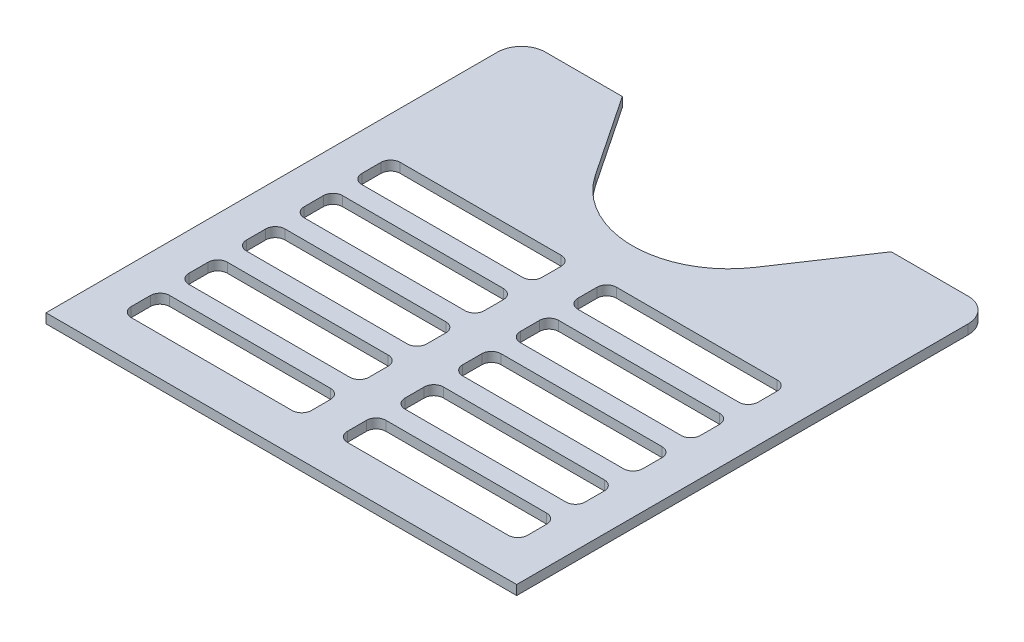
SolidWorks part; units mm, degrees
material "PVC hart"
ref_plane "Ebene vorne" through (0, 0, 0) normal (0, 0, 1) x (1, 0, 0)
ref_plane "Ebene oben" through (0, 0, 0) normal (0, 1, 0) x (1, 0, 0)
ref_plane "Ebene rechts" through (0, 0, 0) normal (1, 0, 0) x (0, 0, -1)
sketch "Skizze2" plane through (0, 0, 0) normal (0, 1, 0) x (1, 0, 0)
  line L0 (0, 82.3632) -> (0, -81.2206) construction
  line L6 (-44, 50) -> (-28, 50)
  line L7 (-28, 50) -> (-16.6199, 33)
  line L8 (28, 50) -> (16.6199, 33)
  line L9 (44, 50) -> (28, 50)
  line L10 (-49, -49) -> (-49, 45)
  line L11 (49, -49) -> (49, 45)
  line L12 (-49, -49) -> (49, -49)
  arc A0 (-16.6199, 33) -> (16.6199, 33) centre (0, 44.1257) ccw
  arc A1 (49, 45) -> (44, 50) centre (44, 45) ccw
  arc A2 (-49, 45) -> (-44, 50) centre (-44, 45) cw
  point P0 (0, 0)
  point P3 (49, 50)
  point P16 (-49, 50)
  dimension "D1" = 20
  dimension "D8" = 5
  dimension "D2" = 49
  dimension "D3" = 99
  dimension "D4" = 21
  dimension "D5" = 17
  dimension "D6" = 49
  dimension "D7" = 49
extrude "Aufsatz-Linear austragen2" add sketch "Skizze2" along normal blind 2
sketch "Skizze3" plane through (0, 2, 0) normal (0, 1, 0) x (1, 0, 0)
  line L0 (0, 51.615) -> (0, -55.1924) construction
  line L1 (-28, 50) -> (-44, 50) construction
  line L2 (-39.25, 15) -> (-5.75, 15)
  line L3 (-41.25, 13) -> (-41.25, 9)
  line L4 (-39.25, 7) -> (-5.75, 7)
  line L5 (-3.75, 13) -> (-3.75, 9)
  line L6 (-41.25, 15) -> (-3.75, 7) construction
  line L7 (-41.25, 7) -> (-3.75, 15) construction
  line L36 (3.75, 13) -> (3.75, 9)
  line L37 (5.75, 15) -> (39.25, 15)
  line L38 (41.25, 13) -> (41.25, 9)
  line L39 (5.75, 7) -> (39.25, 7)
  line L40 (3.75, 1) -> (3.75, -3)
  line L41 (5.75, 3) -> (39.25, 3)
  line L42 (41.25, 1) -> (41.25, -3)
  line L43 (5.75, -5) -> (39.25, -5)
  line L44 (3.75, -11) -> (3.75, -15)
  line L45 (5.75, -9) -> (39.25, -9)
  line L46 (41.25, -11) -> (41.25, -15)
  line L47 (5.75, -17) -> (39.25, -17)
  line L48 (3.75, -23) -> (3.75, -27)
  line L49 (5.75, -21) -> (39.25, -21)
  line L50 (41.25, -23) -> (41.25, -27)
  line L51 (5.75, -29) -> (39.25, -29)
  line L52 (3.75, -35) -> (3.75, -39)
  line L53 (5.75, -33) -> (39.25, -33)
  line L54 (41.25, -35) -> (41.25, -39)
  line L55 (5.75, -41) -> (39.25, -41)
  line L56 (-41.25, 1) -> (-41.25, -3)
  line L57 (-39.25, 3) -> (-5.75, 3)
  line L58 (-3.75, 1) -> (-3.75, -3)
  line L59 (-39.25, -5) -> (-5.75, -5)
  line L60 (-41.25, -11) -> (-41.25, -15)
  line L61 (-39.25, -9) -> (-5.75, -9)
  line L62 (-3.75, -11) -> (-3.75, -15)
  line L63 (-39.25, -17) -> (-5.75, -17)
  line L64 (-41.25, -23) -> (-41.25, -27)
  line L65 (-39.25, -21) -> (-5.75, -21)
  line L66 (-3.75, -23) -> (-3.75, -27)
  line L67 (-39.25, -29) -> (-5.75, -29)
  line L68 (-41.25, -35) -> (-41.25, -39)
  line L69 (-39.25, -33) -> (-5.75, -33)
  line L70 (-3.75, -35) -> (-3.75, -39)
  line L71 (-39.25, -41) -> (-5.75, -41)
  arc A0 (41.25, 9) -> (39.25, 7) centre (39.25, 9) cw
  arc A1 (39.25, 15) -> (41.25, 13) centre (39.25, 13) cw
  arc A2 (3.75, 13) -> (5.75, 15) centre (5.75, 13) cw
  arc A3 (3.75, 9) -> (5.75, 7) centre (5.75, 9) ccw
  arc A4 (3.75, -3) -> (5.75, -5) centre (5.75, -3) ccw
  arc A5 (3.75, 1) -> (5.75, 3) centre (5.75, 1) cw
  arc A6 (39.25, 3) -> (41.25, 1) centre (39.25, 1) cw
  arc A7 (41.25, -3) -> (39.25, -5) centre (39.25, -3) cw
  arc A8 (39.25, -9) -> (41.25, -11) centre (39.25, -11) cw
  arc A9 (41.25, -15) -> (39.25, -17) centre (39.25, -15) cw
  arc A10 (3.75, -15) -> (5.75, -17) centre (5.75, -15) ccw
  arc A11 (3.75, -11) -> (5.75, -9) centre (5.75, -11) cw
  arc A12 (3.75, -27) -> (5.75, -29) centre (5.75, -27) ccw
  arc A13 (3.75, -23) -> (5.75, -21) centre (5.75, -23) cw
  arc A14 (39.25, -21) -> (41.25, -23) centre (39.25, -23) cw
  arc A15 (41.25, -27) -> (39.25, -29) centre (39.25, -27) cw
  arc A16 (41.25, -39) -> (39.25, -41) centre (39.25, -39) cw
  arc A17 (39.25, -33) -> (41.25, -35) centre (39.25, -35) cw
  arc A18 (3.75, -39) -> (5.75, -41) centre (5.75, -39) ccw
  arc A19 (3.75, -35) -> (5.75, -33) centre (5.75, -35) cw
  arc A20 (-5.75, -33) -> (-3.75, -35) centre (-5.75, -35) cw
  arc A21 (-3.75, -39) -> (-5.75, -41) centre (-5.75, -39) cw
  arc A22 (-41.25, -39) -> (-39.25, -41) centre (-39.25, -39) ccw
  arc A23 (-41.25, -35) -> (-39.25, -33) centre (-39.25, -35) cw
  arc A24 (-5.75, -21) -> (-3.75, -23) centre (-5.75, -23) cw
  arc A25 (-3.75, -27) -> (-5.75, -29) centre (-5.75, -27) cw
  arc A26 (-41.25, -27) -> (-39.25, -29) centre (-39.25, -27) ccw
  arc A27 (-41.25, -23) -> (-39.25, -21) centre (-39.25, -23) cw
  arc A28 (-3.75, -15) -> (-5.75, -17) centre (-5.75, -15) cw
  arc A29 (-5.75, -9) -> (-3.75, -11) centre (-5.75, -11) cw
  arc A30 (-41.25, -15) -> (-39.25, -17) centre (-39.25, -15) ccw
  arc A31 (-41.25, -11) -> (-39.25, -9) centre (-39.25, -11) cw
  arc A32 (-3.75, -3) -> (-5.75, -5) centre (-5.75, -3) cw
  arc A33 (-5.75, 3) -> (-3.75, 1) centre (-5.75, 1) cw
  arc A34 (-41.25, -3) -> (-39.25, -5) centre (-39.25, -3) ccw
  arc A35 (-41.25, 1) -> (-39.25, 3) centre (-39.25, 1) cw
  arc A36 (-5.75, 7) -> (-3.75, 9) centre (-5.75, 9) ccw
  arc A37 (-41.25, 9) -> (-39.25, 7) centre (-39.25, 9) ccw
  arc A38 (-39.25, 15) -> (-41.25, 13) centre (-39.25, 13) ccw
  arc A39 (-5.75, 15) -> (-3.75, 13) centre (-5.75, 13) cw
  point P3 (-22.5, 11)
  dimension "D7" = 2
  dimension "D1" = 37.5
  dimension "D2" = 8
  dimension "D3" = 22.5
  dimension "D4" = 35
  dimension "D5" = 2
  dimension "D6" = 5
extrude "Schnitt-Linear austragen2" cut sketch "Skizze3" against normal up to surface (2 mm away) up to face at (0, 0, -25.1197)
